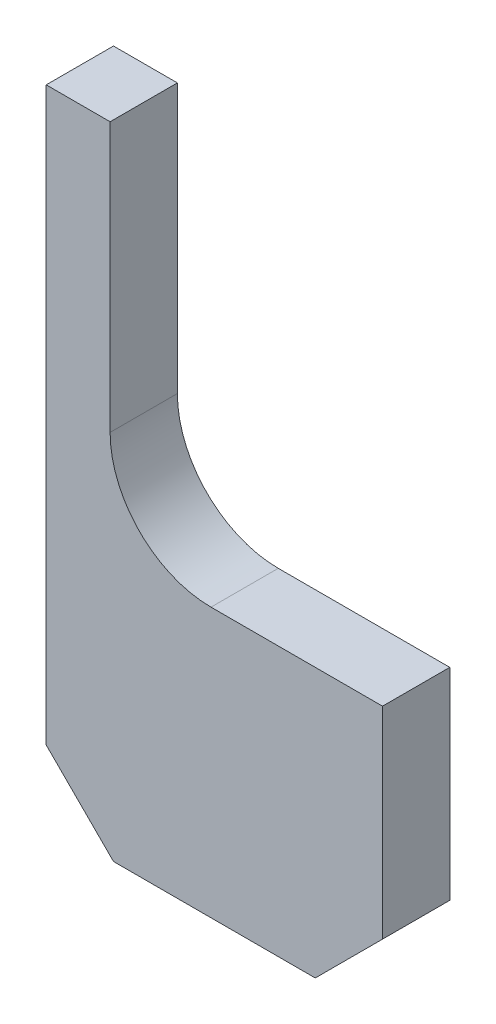
SolidWorks part; units mm, degrees
ref_plane "前视基准面" through (0, 0, 0) normal (0, 0, 1) x (1, 0, 0)
ref_plane "上视基准面" through (0, 0, 0) normal (0, 1, 0) x (1, 0, 0)
ref_plane "右视基准面" through (0, 0, 0) normal (1, 0, 0) x (0, 0, -1)
sketch "草图1" plane through (0, 0, 0) normal (0, 0, 1) x (1, 0, 0)
  line L0 (0, 0) -> (19, 0)
  line L1 (19, 0) -> (19, -80)
  line L2 (49, -110) -> (100, -110)
  line L3 (100, -110) -> (100, -190)
  line L4 (100, -190) -> (0, -190)
  line L5 (0, -190) -> (0, 0)
  arc A0 (19, -80) -> (49, -110) centre (49, -80) ccw
  dimension "D5" = 30
  dimension "D1" = 190
  dimension "D2" = 100
  dimension "D3" = 80
  dimension "D4" = 19
extrude "凸台-拉伸1" add sketch "草图1" along normal blind 20
chamfer "倒角1" distance 20 angle 45 2 edges at (100, -190, 10) (0, -190, 10)
